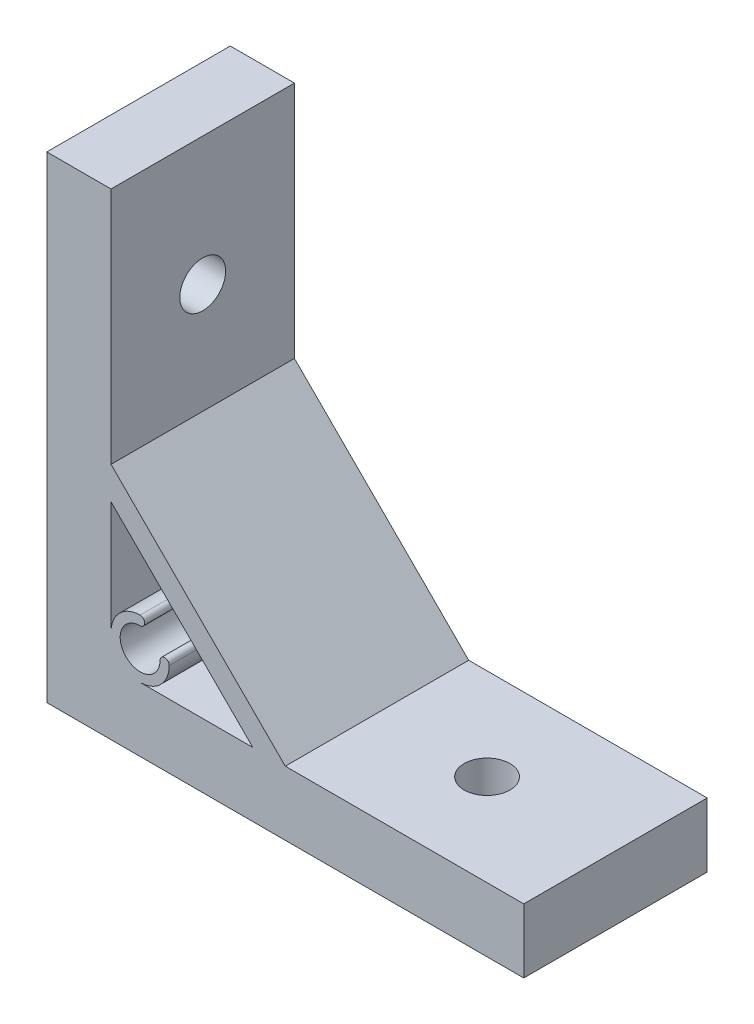
SolidWorks part; units mm, degrees
ref_plane "Front Plane" through (0, 0, 0) normal (0, 0, 1) x (1, 0, 0)
ref_plane "Top Plane" through (0, 0, 0) normal (0, 1, 0) x (1, 0, 0)
ref_plane "Right Plane" through (0, 0, 0) normal (1, 0, 0) x (0, 0, -1)
sketch "Sketch1" plane through (0, 0, 0) normal (0, 0, 1) x (1, 0, 0)
  line L0 (0, 0) -> (0, 78)
  line L1 (0, 0) -> (78, 0)
  line L2 (0, 78) -> (7, 78)
  line L3 (7, 78) -> (7, 26)
  line L4 (7, 26) -> (26, 7)
  line L5 (26, 7) -> (78, 7)
  line L6 (78, 7) -> (78, 0)
  line L7 (7, 22.4645) -> (22.4645, 7)
  line L8 (7, 22.4645) -> (7, 10.175)
  line L9 (10.175, 7) -> (22.4645, 7)
  line L10 (10.175, 13.35) -> (10.175, 12.35) construction
  line L11 (12.35, 10.175) -> (13.35, 10.175) construction
  line L12 (52, 7) -> (52, 0)
  line L13 (7, 52) -> (0, 52)
  arc A0 (10.175, 7) -> (13.35, 10.175) centre (10.175, 10.175) ccw
  arc A1 (10.175, 12.35) -> (12.35, 10.175) centre (10.175, 10.175) ccw
  arc A2 (10.175, 12.35) -> (10.175, 13.35) centre (10.175, 12.85) ccw
  arc A3 (13.35, 10.175) -> (12.35, 10.175) centre (12.85, 10.175) ccw
  arc A4 (10.175, 13.35) -> (7, 10.175) centre (10.175, 10.175) ccw
  point P10 (14.7322, 14.7322)
  dimension "D6" = 6.35
  dimension "D7" = 1
  dimension "D1" = 78
  dimension "D2" = 78
  dimension "D3" = 7
  dimension "D4" = 52
  dimension "D5" = 2.5
extrude "Boss-Extrude1" add sketch "Sketch1" along normal blind 20 contours L3 L13 L0 L1 L12 L5 L4 A2 A4 L8 L7 L9 A0 A3 A1
sketch "Sketch2" plane through (7, 0, 0) normal (1, 0, 0) x (0, 0, -1)
  line L0 (-10, 78) -> (-10, 26)
  line L2 (-20, 26) -> (0, 26) construction
  circle A0 centre (-10, 38) radius 2.5
  circle A1 centre (-10, 68) radius 2.5
  point P10 (0, 0)
  point P11 (0, 0)
  dimension "D1" = 5
  dimension "D2" = 30
  dimension "D3" = 10
  dimension "D4" = 12
extrude "Cut-Extrude1" cut sketch "Sketch2" against normal up to surface (7 mm away) contours L0 A0 | L0 A0 up to face at (0, 26, 10)
ref_plane "Plane1" through (0, 0, 0) normal (0.7071, -0.7071, 0) x (0, 0, -1)
mirror "Mirror4" about plane through (0, 0, 0) normal (0.7071, -0.7071, 0) of "Cut-Extrude1"
